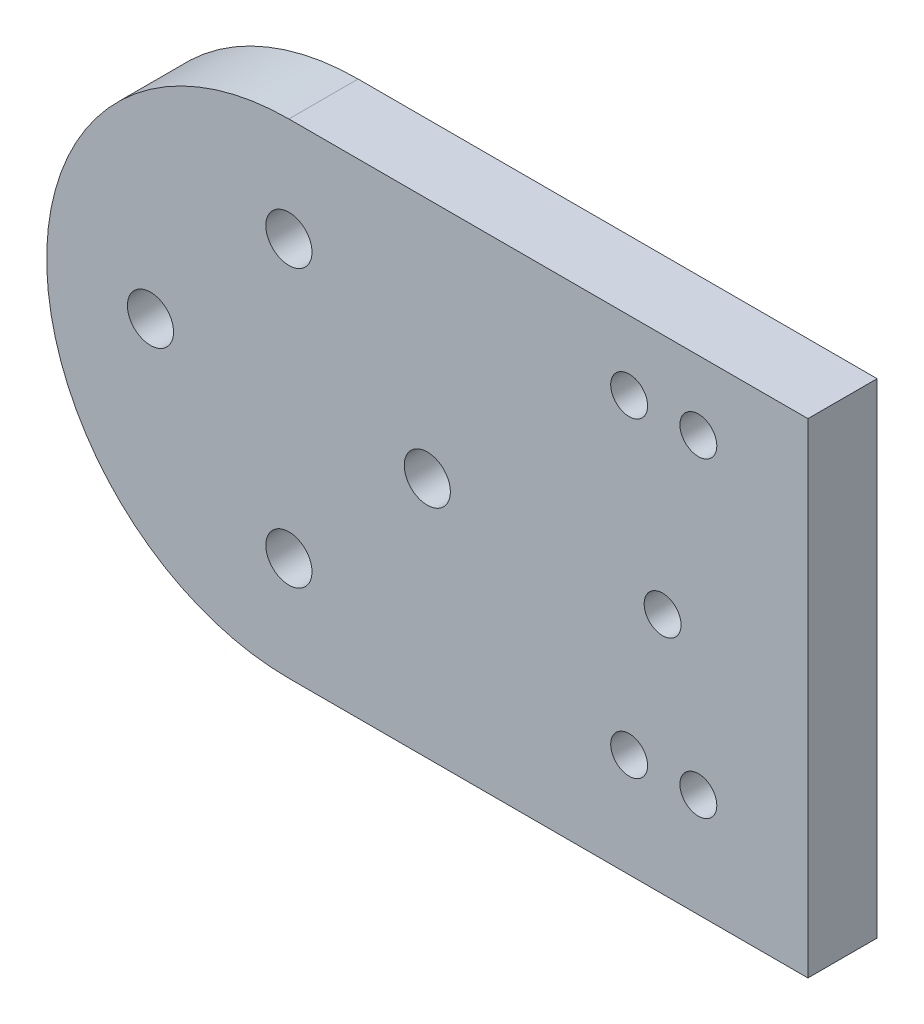
SolidWorks part; units mm, degrees
ref_plane "前视基准面" through (0, 0, 0) normal (0, 0, 1) x (1, 0, 0)
ref_plane "上视基准面" through (0, 0, 0) normal (0, 1, 0) x (1, 0, 0)
ref_plane "右视基准面" through (0, 0, 0) normal (1, 0, 0) x (0, 0, -1)
sketch "草图1" plane through (0, 0, 0) normal (0, 0, 1) x (1, 0, 0)
  line L0 (0, 0) -> (-23.8025, 0) construction
  line L1 (0, 21) -> (25, 21)
  line L2 (0, 21) -> (0, -21)
  line L3 (0, -21) -> (25, -21)
  line L4 (25, 21) -> (25, -21)
  line L5 (29.5, 18.7564) -> (29.5, 5.9546) construction
  line L6 (25, 21) -> (40, 21)
  line L7 (25, 21) -> (25, -21)
  line L8 (25, -21) -> (40, -21)
  line L9 (40, 21) -> (40, -21)
  line L11 (40, 21) -> (45, 21)
  line L12 (40, 21) -> (40, -21)
  line L13 (40, -21) -> (45, -21)
  line L14 (45, 21) -> (45, -21)
  circle A0 centre (0, 0) radius 21
  circle A1 centre (0, 0) radius 12
  circle A2 centre (0, 12) radius 2
  circle A3 centre (0, -12) radius 2
  circle A4 centre (-12, 0) radius 2
  circle A5 centre (12, 0) radius 2
  circle A6 centre (29.5, 15) radius 1.6
  circle A7 centre (35.5, 15) radius 1.6
  circle A8 centre (35.5, -12) radius 1.6
  circle A9 centre (29.5, -12) radius 1.6
  circle A10 centre (32.4, 0) radius 1.6
  point P20 (29.5, 21)
  dimension "D1" = 42
  dimension "D3" = 24
  dimension "D4" = 4
  dimension "D8" = 3.2
  dimension "D12" = 3.2
  dimension "D2" = 25
  dimension "D5" = 15
  dimension "D6" = 4.5
  dimension "D7" = 6
  dimension "D11" = 7.6
  dimension "D13" = 6
  dimension "D14" = 9
  dimension "D15" = 4.5
  dimension "D16" = 5
  dimension "D9" = 2
  dimension "D10" = 2
extrude "凸台-拉伸1" add sketch "草图1" along normal blind 6 contours A4 A1 A2 L2 A0 A3 | A4 A1 A3 L2 A2 | A5 A1 A2 L2 A3 | A5 A1 A3 L2 A0 A2 | A0 L3 L4 L1 | L9 L6 L4 L8 A10 A9 A8 A7 A6 | L14 L11 L9 L13
